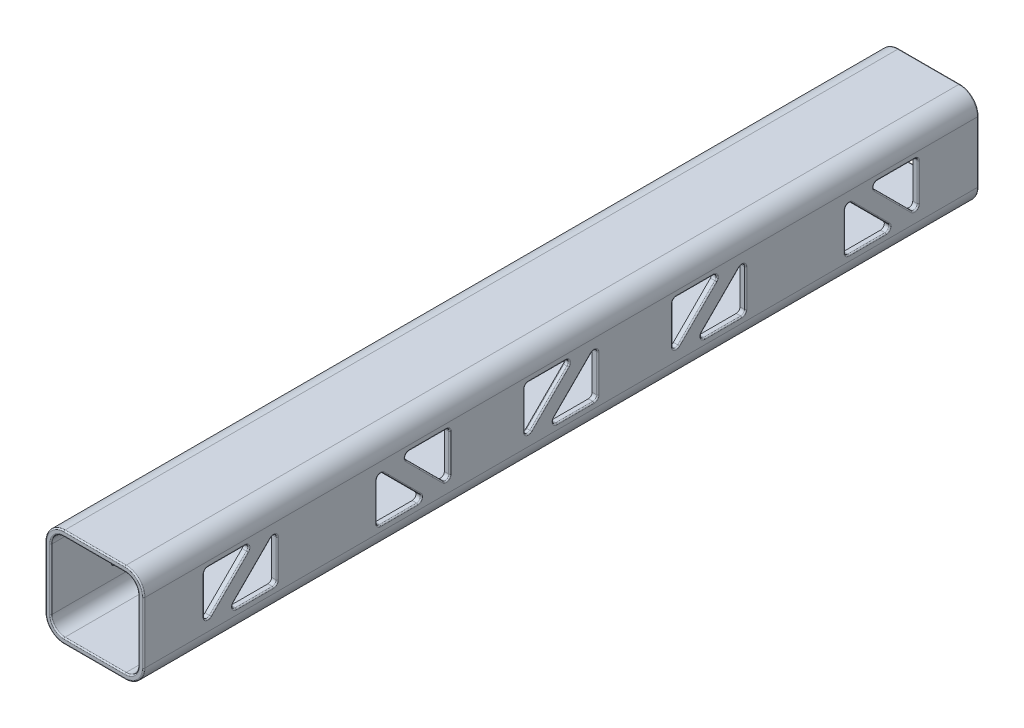
SolidWorks part; units mm, degrees
material "moto_yellow"
ref_plane "Front Plane" through (0, 0, 0) normal (0, 0, 1) x (1, 0, 0)
ref_plane "Top Plane" through (0, 0, 0) normal (0, 1, 0) x (1, 0, 0)
ref_plane "Right Plane" through (0, 0, 0) normal (1, 0, 0) x (0, 0, -1)
sketch "Sketch2" plane through (0, 0, 0) normal (0, 0, 1) x (1, 0, 0)
  line L0 (-24.5, 35.024) -> (24.5, 35.024)
  line L1 (-24.5, 39.5) -> (24.5, 39.5)
  line L2 (-39.5, 24.5) -> (-39.5, -24.5)
  line L3 (-24.5, -39.5) -> (24.5, -39.5)
  line L4 (39.5, 24.5) -> (39.5, -24.5)
  line L5 (-39.5, 39.5) -> (39.5, -39.5) construction
  line L6 (-39.5, -39.5) -> (39.5, 39.5) construction
  line L7 (35.024, 24.5) -> (35.024, -24.5)
  line L8 (-24.5, -35.024) -> (24.5, -35.024)
  line L9 (-35.024, 24.5) -> (-35.024, -24.5)
  arc A0 (-39.5, -24.5) -> (-24.5, -39.5) centre (-24.5, -24.5) ccw
  arc A1 (24.5, -39.5) -> (39.5, -24.5) centre (24.5, -24.5) ccw
  arc A2 (24.5, 39.5) -> (39.5, 24.5) centre (24.5, 24.5) cw
  arc A3 (-24.5, 39.5) -> (-39.5, 24.5) centre (-24.5, 24.5) ccw
  arc A4 (24.5, 35.024) -> (35.024, 24.5) centre (24.5, 24.5) cw
  arc A5 (24.5, -35.024) -> (35.024, -24.5) centre (24.5, -24.5) ccw
  arc A6 (-35.024, -24.5) -> (-24.5, -35.024) centre (-24.5, -24.5) ccw
  arc A7 (-24.5, 35.024) -> (-35.024, 24.5) centre (-24.5, 24.5) ccw
  point P0 (0, 0)
  dimension "D3" = 15
  dimension "D1" = 79
  dimension "D2" = 79
  dimension "D4" = 4.476
extrude "Boss-Extrude1" add sketch "Sketch2" along normal mid plane 670
sketch "Sketch3" plane through (0, 0, 0) normal (1, 0, 0) x (0, 0, -1)
  line L1 (-26.2816, 20.2069) -> (3.4757, 20.2069)
  line L5 (24.2027, 15.0856) -> (-5.5546, -14.6717)
  line L8 (-3.4333, -19.7931) -> (26.324, -19.7931)
  line L9 (29.324, 12.9643) -> (29.324, -16.7931)
  line L10 (5.597, 15.0856) -> (-24.1603, -14.6717)
  line L11 (-29.2816, -12.5504) -> (-29.2816, 17.2069)
  line L12 (-59.2816, 4.7964) -> (-59.2816, -5.0535)
  line L13 (0.0212, 0.2069) -> (0.0212, -6.3733)
  line L14 (-147.8873, 12.9643) -> (-147.8873, -16.7931)
  line L15 (-115.13, -19.7931) -> (-144.8873, -19.7931)
  line L16 (-142.766, 15.0856) -> (-113.0087, -14.6717)
  line L17 (-92.2816, 20.2069) -> (-122.039, 20.2069)
  line L18 (-89.2816, -12.5504) -> (-89.2816, 17.2069)
  line L19 (-124.1603, 15.0856) -> (-94.403, -14.6717)
  line L20 (-187.8873, 2.1721) -> (-187.8873, -8.7373)
  line L21 (-283.493, 20.2069) -> (-253.7357, 20.2069)
  line L22 (-286.493, -12.5504) -> (-286.493, 17.2069)
  line L23 (-251.6143, 15.0856) -> (-281.3717, -14.6717)
  line L24 (-260.6447, -19.7931) -> (-230.8873, -19.7931)
  line L25 (-233.0087, 15.0856) -> (-262.766, -14.6717)
  line L26 (-227.8873, 12.9643) -> (-227.8873, -16.7931)
  line L27 (251.6567, 15.0856) -> (281.4141, -14.6717)
  line L28 (283.5354, 20.2069) -> (253.778, 20.2069)
  line L29 (286.5354, -12.5504) -> (286.5354, 17.2069)
  line L30 (260.6871, -19.7931) -> (230.9297, -19.7931)
  line L31 (233.051, 15.0856) -> (262.8084, -14.6717)
  line L32 (227.9297, 12.9643) -> (227.9297, -16.7931)
  line L33 (147.9297, 12.9643) -> (147.9297, -16.7931)
  line L34 (115.1724, -19.7931) -> (144.9297, -19.7931)
  line L35 (142.8084, 15.0856) -> (113.051, -14.6717)
  line L36 (124.2027, 15.0856) -> (94.4454, -14.6717)
  line L37 (92.324, 20.2069) -> (122.0814, 20.2069)
  line L38 (89.324, -12.5504) -> (89.324, 17.2069)
  arc A0 (-5.5546, -14.6717) -> (-3.4333, -19.7931) centre (-3.4333, -16.7931) ccw
  arc A1 (26.324, -19.7931) -> (29.324, -16.7931) centre (26.324, -16.7931) ccw
  arc A2 (24.2027, 15.0856) -> (29.324, 12.9643) centre (26.324, 12.9643) cw
  arc A3 (-26.2816, 20.2069) -> (-29.2816, 17.2069) centre (-26.2816, 17.2069) ccw
  arc A4 (-29.2816, -12.5504) -> (-24.1603, -14.6717) centre (-26.2816, -12.5504) ccw
  arc A5 (3.4757, 20.2069) -> (5.597, 15.0856) centre (3.4757, 17.2069) cw
  arc A6 (-144.8873, -19.7931) -> (-147.8873, -16.7931) centre (-144.8873, -16.7931) cw
  arc A7 (-113.0087, -14.6717) -> (-115.13, -19.7931) centre (-115.13, -16.7931) cw
  arc A8 (-142.766, 15.0856) -> (-147.8873, 12.9643) centre (-144.8873, 12.9643) ccw
  arc A9 (-122.039, 20.2069) -> (-124.1603, 15.0856) centre (-122.039, 17.2069) ccw
  arc A10 (-92.2816, 20.2069) -> (-89.2816, 17.2069) centre (-92.2816, 17.2069) cw
  arc A11 (-89.2816, -12.5504) -> (-94.403, -14.6717) centre (-92.2816, -12.5504) cw
  arc A12 (-253.7357, 20.2069) -> (-251.6143, 15.0856) centre (-253.7357, 17.2069) cw
  arc A13 (-283.493, 20.2069) -> (-286.493, 17.2069) centre (-283.493, 17.2069) ccw
  arc A14 (-286.493, -12.5504) -> (-281.3717, -14.6717) centre (-283.493, -12.5504) ccw
  arc A15 (-262.766, -14.6717) -> (-260.6447, -19.7931) centre (-260.6447, -16.7931) ccw
  arc A16 (-230.8873, -19.7931) -> (-227.8873, -16.7931) centre (-230.8873, -16.7931) ccw
  arc A17 (-233.0087, 15.0856) -> (-227.8873, 12.9643) centre (-230.8873, 12.9643) cw
  arc A18 (253.778, 20.2069) -> (251.6567, 15.0856) centre (253.778, 17.2069) ccw
  arc A19 (283.5354, 20.2069) -> (286.5354, 17.2069) centre (283.5354, 17.2069) cw
  arc A20 (286.5354, -12.5504) -> (281.4141, -14.6717) centre (283.5354, -12.5504) cw
  arc A21 (230.9297, -19.7931) -> (227.9297, -16.7931) centre (230.9297, -16.7931) cw
  arc A22 (262.8084, -14.6717) -> (260.6871, -19.7931) centre (260.6871, -16.7931) cw
  arc A23 (233.051, 15.0856) -> (227.9297, 12.9643) centre (230.9297, 12.9643) ccw
  arc A24 (142.8084, 15.0856) -> (147.9297, 12.9643) centre (144.9297, 12.9643) cw
  arc A25 (144.9297, -19.7931) -> (147.9297, -16.7931) centre (144.9297, -16.7931) ccw
  arc A26 (113.051, -14.6717) -> (115.1724, -19.7931) centre (115.1724, -16.7931) ccw
  arc A27 (89.324, -12.5504) -> (94.4454, -14.6717) centre (92.324, -12.5504) ccw
  arc A28 (122.0814, 20.2069) -> (124.2027, 15.0856) centre (122.0814, 17.2069) cw
  arc A29 (92.324, 20.2069) -> (89.324, 17.2069) centre (92.324, 17.2069) ccw
  point P0 (-28.5847, -2.4354)
  point P11 (-10.676, -19.7931)
  point P14 (29.324, -19.7931)
  point P17 (29.324, 20.2069)
  point P20 (-29.2816, 20.2069)
  point P23 (-29.2816, -19.7931)
  point P26 (10.7184, 20.2069)
  dimension "D5" = 3
  dimension "D1" = 40
  dimension "D2" = 40
  dimension "D3" = 40
  dimension "D4" = 40
  dimension "D6" = 30
  dimension "D7" = 40
extrude "Cut-Extrude1" cut sketch "Sketch3" against normal mid plane 91 contours L22 A14 L23 A12 L21 A13 | A17 L25 A15 L24 A16 L26 | L16 A8 L14 A6 L15 A7 | A11 L18 A10 L17 A9 L19 | A5 L1 A3 L11 A4 L10 | A2 L5 A0 L8 A1 L9 | L35 A26 L34 A25 L33 A24 | L37 A29 L38 A27 L36 A28 | L31 A23 L32 A21 L30 A22 | A20 L29 A19 L28 A18 L27
fillet "Fillet1" radius 1 32 edges at (35.1066, 35.1066, -335) (39.5, 0, -335) (35.1066, -35.1066, -335) (0, -39.5, -335) (-35.1066, -35.1066, -335) (-39.5, 0, -335) (-35.1066, 35.1066, -335) (31.9416, 31.9416, -335) (35.024, 0, -335) (31.9416, -31.9416, -335) (0, -35.024, -335) (-31.9416, -31.9416, -335) (-35.024, 0, -335) (-31.9416, 31.9416, -335) (31.9416, 31.9416, 335) (35.024, 0, 335) (31.9416, -31.9416, 335) (0, -35.024, 335) (-31.9416, -31.9416, 335) (-35.024, 0, 335) (-31.9416, 31.9416, 335) (39.5, 0, 335) (35.1066, -35.1066, 335) (0, -39.5, 335) (-35.1066, -35.1066, 335) (-39.5, 0, 335) (-35.1066, 35.1066, 335) (0, 39.5, -335) (0, 35.024, -335) (0, 35.024, 335) (35.1066, 35.1066, 335) (0, 39.5, 335)
fillet "Fillet2" radius 1 66 edges at (39.5, 0.2069, 9.2816) (39.5, 18.355, -6.2473) (39.5, 20.2069, 11.403) (39.5, 19.3283, 28.403) (39.5, 2.3283, 29.2816) (35.024, 0.2069, 9.2816) (35.024, 18.355, -6.2473) (35.024, 20.2069, 11.403) (35.024, 19.3283, 28.403) (35.024, 2.3283, 29.2816) (39.5, -15.322, -284.6835) (39.5, 2.3283, -286.5354) (39.5, 19.3283, -285.6567) (39.5, 20.2069, -268.6567) (39.5, 18.355, -251.0064) (39.5, -17.9411, -263.4587) (39.5, -19.7931, -245.8084) (39.5, -18.9144, -228.8084) (39.5, -1.9144, -227.9297) (39.5, 15.7359, -229.7817) (39.5, -15.322, -91.176) (39.5, 2.3283, -89.324) (39.5, 19.3283, -90.2027) (39.5, 20.2069, -107.2027) (39.5, 18.355, -124.853) (39.5, -17.9411, -112.4007) (39.5, -19.7931, -130.051) (39.5, -18.9144, -147.051) (39.5, -1.9144, -147.9297) (39.5, 15.7359, -146.0778) (39.5, -18.9144, -28.4454) (39.5, -1.9144, -29.324) (39.5, 15.7359, -27.4721) (39.5, 0.2069, -9.324) (39.5, -17.9411, 6.205) (39.5, 19.3283, 90.1603) (39.5, 20.2069, 107.1603) (39.5, 18.355, 124.8106) (39.5, 0.2069, 109.2816) (39.5, -15.322, 91.1336) (39.5, -18.9144, 147.0087) (39.5, -19.7931, 130.0087) (39.5, -17.9411, 112.3583) (39.5, 0.2069, 127.8873) (39.5, 15.7359, 146.0354) (39.5, -18.9144, 228.766) (39.5, -19.7931, 245.766) (39.5, -17.9411, 263.4163) (39.5, 0.2069, 247.8873) (39.5, 15.7359, 229.7393) (39.5, -15.322, 284.6411) (39.5, 2.3283, 286.493) (39.5, 19.3283, 285.6143) (39.5, 20.2069, 268.6143) (39.5, 18.355, 250.964) (39.5, -15.322, 27.4297) (35.024, -15.322, 27.4297) (39.5, 0.2069, -266.5354) (39.5, 0.2069, -247.9297) (39.5, 0.2069, -109.324) (39.5, 0.2069, -127.9297) (39.5, -19.7931, -11.4454) (39.5, 2.3283, 89.2816) (39.5, -1.9144, 147.8873) (39.5, -1.9144, 227.8873) (39.5, 0.2069, 266.493)
fillet "Fillet3" radius 1 60 edges at (-39.5, -1.9144, -29.324) (-39.5, -18.9144, -28.4454) (-39.5, -19.7931, -11.4454) (-39.5, -17.9411, 6.205) (-39.5, 0.2069, -9.324) (-39.5, 15.7359, -27.4721) (-39.5, -1.9144, -147.9297) (-39.5, -18.9144, -147.051) (-39.5, -19.7931, -130.051) (-39.5, -17.9411, -112.4007) (-39.5, 0.2069, -127.9297) (-39.5, 15.7359, -146.0778) (-39.5, -17.9411, -263.4587) (-39.5, -19.7931, -245.8084) (-39.5, -18.9144, -228.8084) (-39.5, -1.9144, -227.9297) (-39.5, 15.7359, -229.7817) (-39.5, 0.2069, -247.9297) (-39.5, -17.9411, 112.3583) (-39.5, -19.7931, 130.0087) (-39.5, -18.9144, 147.0087) (-39.5, -1.9144, 147.8873) (-39.5, 15.7359, 146.0354) (-39.5, 0.2069, 127.8873) (-39.5, 0.2069, 9.2816) (-39.5, -15.322, 27.4297) (-39.5, 2.3283, 29.2816) (-39.5, 19.3283, 28.403) (-39.5, 20.2069, 11.403) (-39.5, 18.355, -6.2473) (-39.5, 19.3283, 285.6143) (-39.5, 20.2069, 268.6143) (-39.5, 18.355, 250.964) (-39.5, 0.2069, 266.493) (-39.5, -15.322, 284.6411) (-39.5, 2.3283, 286.493) (-39.5, 0.2069, -266.5354) (-39.5, 18.355, -251.0064) (-39.5, 20.2069, -268.6567) (-39.5, 19.3283, -285.6567) (-39.5, 2.3283, -286.5354) (-39.5, -15.322, -284.6835) (-39.5, 0.2069, 109.2816) (-39.5, 18.355, 124.8106) (-39.5, 20.2069, 107.1603) (-39.5, 19.3283, 90.1603) (-39.5, 2.3283, 89.2816) (-39.5, -15.322, 91.1336) (-39.5, -1.9144, 227.8873) (-39.5, -18.9144, 228.766) (-39.5, -19.7931, 245.766) (-39.5, -17.9411, 263.4163) (-39.5, 0.2069, 247.8873) (-39.5, 15.7359, 229.7393) (-39.5, 18.355, -124.853) (-39.5, 0.2069, -109.324) (-39.5, -15.322, -91.176) (-39.5, 2.3283, -89.324) (-39.5, 19.3283, -90.2027) (-39.5, 20.2069, -107.2027)
